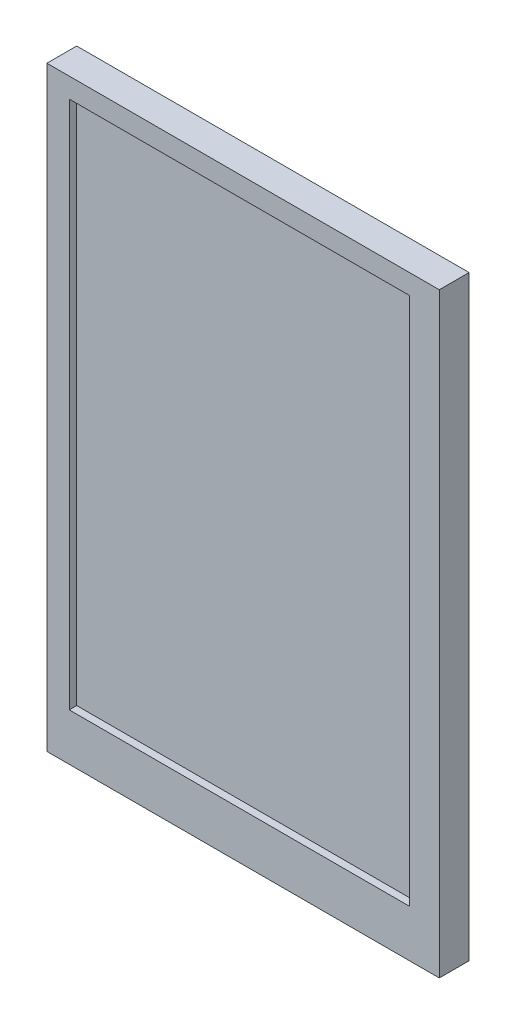
SolidWorks part; units mm, degrees
ref_plane "Front Plane" through (0, 0, 0) normal (1, 0, 0) x (0, 1, 0)
ref_plane "Top Plane" through (0, 0, 0) normal (0, 0, 1) x (0, 1, 0)
ref_plane "Right Plane" through (0, 0, 0) normal (0, 1, 0) x (-1, 0, 0)
sketch "Sketch2" plane through (0, 0, 0) normal (0, 0, 1) x (0, 1, 0)
  line L0 (-2.273, 0) -> (242.273, 0) construction
  line L1 (0, -55) -> (0, 55) construction
  line L2 (0, 160.5777) -> (0, -2.5777) construction
  line L3 (-55, 0) -> (55, 0) construction
  line L5 (-120, 79) -> (120, 79)
  line L6 (-120, 79) -> (-120, -79)
  line L7 (-120, -79) -> (120, -79)
  line L8 (120, 79) -> (120, -79)
  point P13 (0, 79)
  point P14 (120, 0)
  dimension "D1" = 240
  dimension "D2" = 158
extrude "Boss-Extrude1" add sketch "Sketch2" along normal blind 12
sketch "Sketch4" plane through (0, 0, 12) normal (0, 0, 1) x (1, 0, 0)
  line L0 (-79, 120) -> (-79, -120) construction
  line L1 (-70, -101) -> (67, -101)
  line L2 (-70, -101) -> (-70, 112)
  line L3 (-70, 112) -> (67, 112)
  line L4 (67, -101) -> (67, 112)
  line L5 (-79, -120) -> (79, -120) construction
  line L6 (79, 120) -> (-79, 120) construction
  line L7 (79, -120) -> (79, 120) construction
  dimension "D1" = 9
  dimension "D2" = 19
  dimension "D3" = 8
  dimension "D4" = 12
extrude "Cut-Extrude1" cut sketch "Sketch4" against normal blind 3
